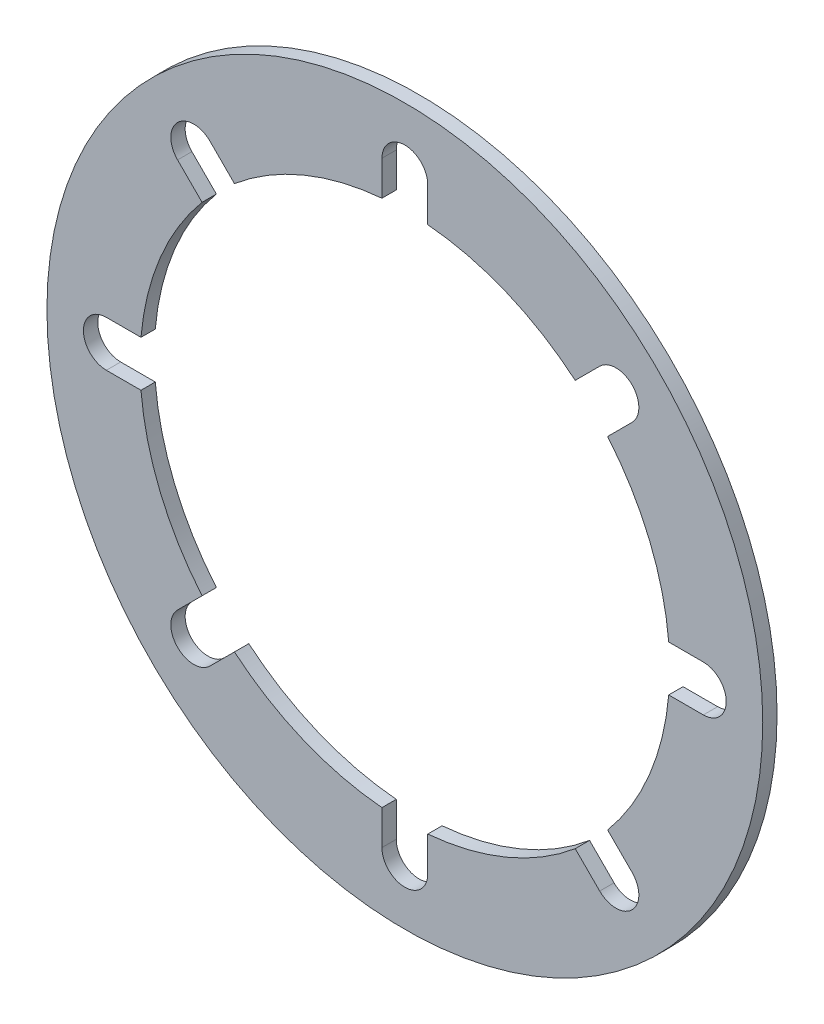
SolidWorks part; units mm, degrees
material "深紫色PETG"
ref_plane "前视基准面" through (0, 0, 0) normal (0, 0, 1) x (1, 0, 0)
ref_plane "上视基准面" through (0, 0, 0) normal (0, 1, 0) x (1, 0, 0)
ref_plane "右视基准面" through (0, 0, 0) normal (1, 0, 0) x (0, 0, -1)
other "Configuration Table"
sketch "草图1" plane through (0, 0, 0) normal (0, 0, 1) x (1, 0, 0)
  line L0 (-1.6, 20.85) -> (-1.6, 18.4307)
  line L1 (1.6, 20.85) -> (1.6, 18.4307)
  line L2 (13.6118, 15.8745) -> (11.9011, 14.1638)
  line L3 (15.8745, 13.6118) -> (14.1638, 11.9011)
  line L4 (20.85, 1.6) -> (18.4307, 1.6)
  line L5 (20.85, -1.6) -> (18.4307, -1.6)
  line L6 (15.8745, -13.6118) -> (14.1638, -11.9011)
  line L7 (13.6118, -15.8745) -> (11.9011, -14.1638)
  line L8 (1.6, -20.85) -> (1.6, -18.4307)
  line L9 (-1.6, -20.85) -> (-1.6, -18.4307)
  line L10 (-13.6118, -15.8745) -> (-11.9011, -14.1638)
  line L11 (-15.8745, -13.6118) -> (-14.1638, -11.9011)
  line L12 (-20.85, -1.6) -> (-18.4307, -1.6)
  line L13 (-20.85, 1.6) -> (-18.4307, 1.6)
  line L14 (-15.8745, 13.6118) -> (-14.1638, 11.9011)
  line L15 (-13.6118, 15.8745) -> (-11.9011, 14.1638)
  arc A0 (-1.6, 18.4307) -> (-11.9011, 14.1638) centre (0, 0) ccw
  circle A1 centre (0, 0) radius 25
  circle A2 centre (0, 0) radius 20.85 construction
  arc A3 (1.6, 20.85) -> (-1.6, 20.85) centre (0, 20.85) ccw
  arc A4 (15.8745, 13.6118) -> (13.6118, 15.8745) centre (14.7432, 14.7432) ccw
  arc A5 (20.85, -1.6) -> (20.85, 1.6) centre (20.85, 0) ccw
  arc A6 (13.6118, -15.8745) -> (15.8745, -13.6118) centre (14.7432, -14.7432) ccw
  arc A7 (-1.6, -20.85) -> (1.6, -20.85) centre (0, -20.85) ccw
  arc A8 (-15.8745, -13.6118) -> (-13.6118, -15.8745) centre (-14.7432, -14.7432) ccw
  arc A9 (-20.85, 1.6) -> (-20.85, -1.6) centre (-20.85, 0) ccw
  arc A10 (-13.6118, 15.8745) -> (-15.8745, 13.6118) centre (-14.7432, 14.7432) ccw
  arc A11 (-14.1638, 11.9011) -> (-18.4307, 1.6) centre (0, 0) ccw
  arc A12 (11.9011, 14.1638) -> (1.6, 18.4307) centre (0, 0) ccw
  arc A13 (18.4307, 1.6) -> (14.1638, 11.9011) centre (0, 0) ccw
  arc A14 (14.1638, -11.9011) -> (18.4307, -1.6) centre (0, 0) ccw
  arc A15 (1.6, -18.4307) -> (11.9011, -14.1638) centre (0, 0) ccw
  arc A16 (-11.9011, -14.1638) -> (-1.6, -18.4307) centre (0, 0) ccw
  arc A17 (-18.4307, -1.6) -> (-14.1638, -11.9011) centre (0, 0) ccw
  point P47 (0, 0)
  dimension "D1" = 37
  dimension "D2" = 41.7
  dimension "D3" = 3.2
  dimension "D4" = 8
extrude "凸台-拉伸1" add sketch "草图1" along normal blind 1
